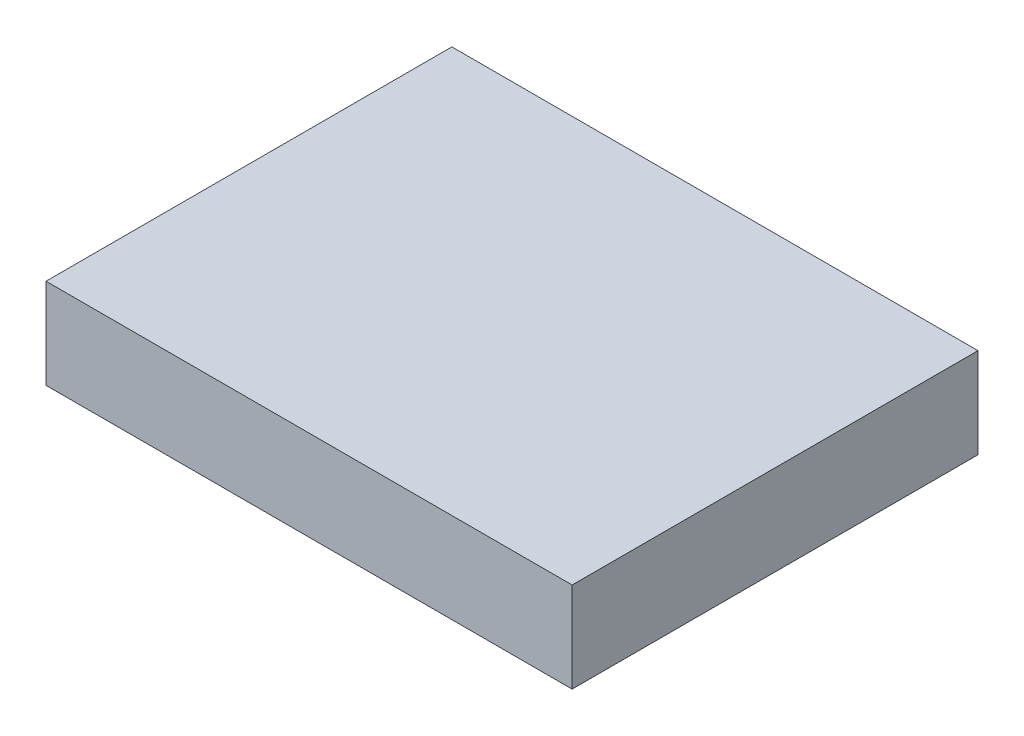
SolidWorks part; units mm, degrees
ref_plane "前视基准面" through (0, 0, 0) normal (0, 0, 1) x (1, 0, 0)
ref_plane "上视基准面" through (0, 0, 0) normal (0, 1, 0) x (1, 0, 0)
ref_plane "右视基准面" through (0, 0, 0) normal (1, 0, 0) x (0, 0, -1)
sketch "草图1" plane through (0, 0, 0) normal (0, 1, 0) x (1, 0, 0)
  line L1 (-35, 27) -> (35, 27)
  line L2 (-35, 27) -> (-35, -27)
  line L3 (-35, -27) -> (35, -27)
  line L4 (35, 27) -> (35, -27)
  line L5 (-35, 27) -> (35, -27) construction
  line L6 (-35, -27) -> (35, 27) construction
  point P0 (0, 0)
  dimension "D1" = 70
  dimension "D2" = 54
extrude "凸台-拉伸1" add sketch "草图1" along normal blind 12
